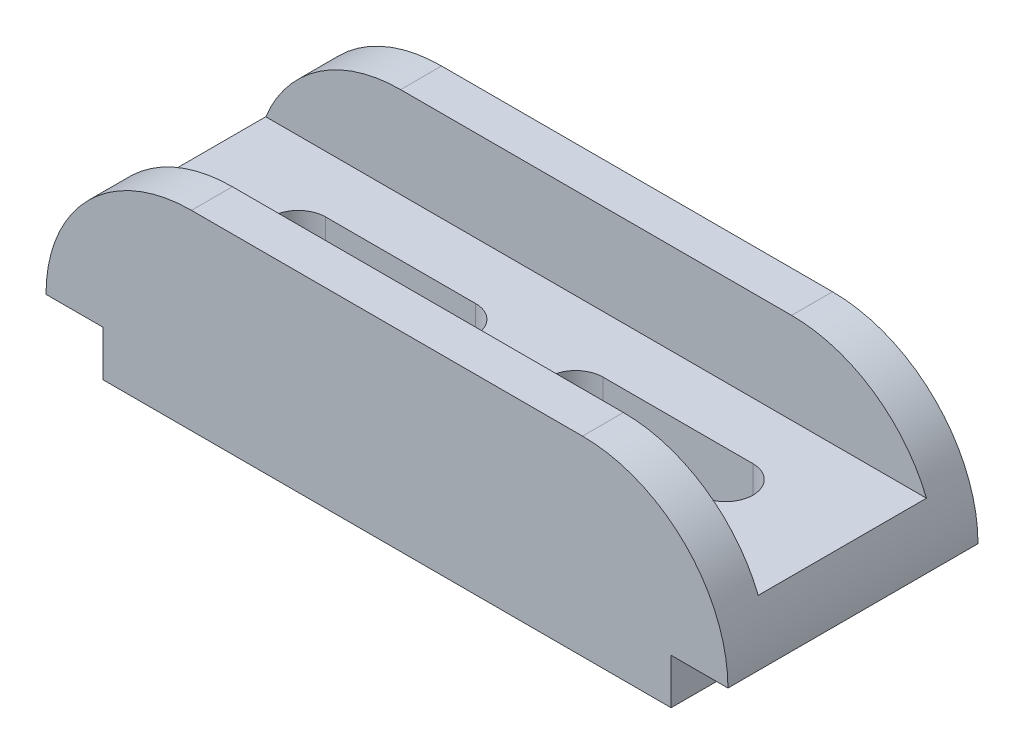
SolidWorks part; units mm, degrees
ref_plane "Front Plane" through (0, 0, 0) normal (0, 0, 1) x (1, 0, 0)
ref_plane "Top Plane" through (0, 0, 0) normal (0, 1, 0) x (1, 0, 0)
ref_plane "Right Plane" through (0, 0, 0) normal (1, 0, 0) x (0, 0, -1)
sketch "Sketch1" plane through (0, 0, 0) normal (0, 0, 1) x (1, 0, 0)
  line L0 (-62.5, 0) -> (62.5, 0)
  line L1 (62.5, 0) -> (62.5, 10)
  line L2 (62.5, 10) -> (75, 10)
  line L3 (43, 42) -> (-43, 42)
  line L4 (0, -7.7842) -> (0, 83.2786) construction
  line L5 (-62.5, 10) -> (-75, 10)
  line L6 (-62.5, 0) -> (-62.5, 10)
  arc A0 (75, 10) -> (43, 42) centre (43, 10) ccw
  arc A1 (-75, 10) -> (-43, 42) centre (-43, 10) cw
  point P10 (36.5081, 41.4615)
  point P11 (62.5, 8.2172)
  point P12 (75, 8.3551)
  point P13 (0, 0)
  point P14 (0, 0)
  point P15 (0, 83.2786)
  point P19 (0, 42)
  point P21 (0, 0)
  dimension "D1" = 62.5
  dimension "D4" = 32
  dimension "D2" = 75
  dimension "D3" = 42
extrude "Boss-Extrude1" add sketch "Sketch1" along normal mid plane 55
sketch "Sketch2" plane through (0, 42, 0) normal (0, 1, 0) x (1, 0, 0)
  line L0 (14, 0) -> (47, 0) construction
  line L5 (-14, 0) -> (-47, 0) construction
  line L6 (-14, 6) -> (-47, 6)
  line L7 (14, 6) -> (47, 6)
  line L8 (14, -6) -> (47, -6)
  line L9 (0, -2.2167) -> (0, 7.0355) construction
  line L10 (-14, -6) -> (-47, -6)
  arc A0 (14, 6) -> (14, -6) centre (14, 0) ccw
  arc A1 (47, -6) -> (47, 6) centre (47, 0) ccw
  arc A2 (-14, 6) -> (-14, -6) centre (-14, 0) cw
  arc A3 (-47, -6) -> (-47, 6) centre (-47, 0) cw
  point P0 (0, 0)
  point P3 (-30.5, 0)
  point P8 (30.5, 0)
  dimension "D2" = 6
  dimension "D1" = 33
  dimension "D3" = 14
sketch "Sketch3" plane through (0, 0, 0) normal (1, 0, 0) x (0, 0, -1)
  line L0 (18.5, 42) -> (18.5, 22)
  line L1 (-27.5, 42) -> (27.5, 42) construction
  line L2 (18.5, 22) -> (-18.5, 22)
  line L3 (-18.5, 22) -> (-18.5, 42)
  line L4 (-18.5, 42) -> (18.5, 42)
  point P6 (0, 22)
  dimension "D1" = 20
  dimension "D2" = 37
extrude "Cut-Extrude1" cut sketch "Sketch3" against normal through all both and the other way through all
extrude "Cut-Extrude2" cut sketch "Sketch2" against normal up to next
